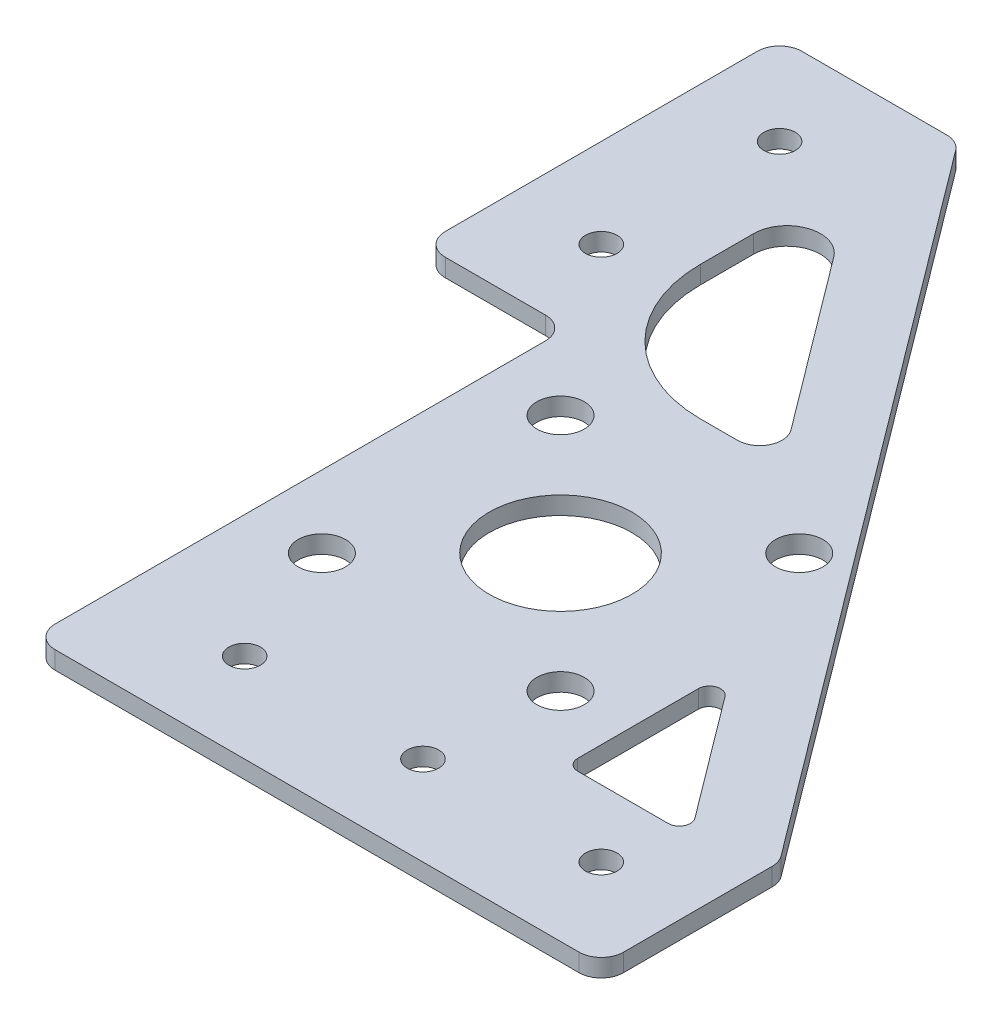
SolidWorks part; units mm, degrees
material "6061-O (SS)"
ref_plane "Front Plane" through (0, 0, 0) normal (0, 0, 1) x (1, 0, 0)
ref_plane "Top Plane" through (0, 0, 0) normal (0, 1, 0) x (1, 0, 0)
ref_plane "Right Plane" through (0, 0, 0) normal (1, 0, 0) x (0, 0, -1)
sketch "Sketch1" plane through (0, 0, 0) normal (0, 1, 0) x (1, 0, 0)
  line L6 (26.3525, 125.73) -> (100.965, 26.2467)
  line L19 (254, 25.4) -> (-431.8, 25.4) construction
  line L22 (254, 0) -> (-431.8, 0) construction
  line L23 (98.425, 0) -> (23.8125, 0)
  line L26 (0, 79.375) -> (0, 123.825)
  line L28 (0, 25.4) -> (0, 787.4) construction
  line L31 (3.175, 127) -> (23.8125, 127)
  line L33 (25.4, 25.4) -> (25.4, 787.4) construction
  line L35 (101.6, 3.175) -> (101.6, 24.3417)
  line L37 (17.4625, 76.2) -> (3.175, 76.2)
  line L38 (20.6375, 73.025) -> (20.6375, 3.175)
  arc A0 (12.7762, 112.2313) -> (12.7762, 116.3687) centre (12.7, 114.3) ccw construction
  arc A1 (12.6238, 90.9687) -> (12.6238, 86.8313) centre (12.7, 88.9) ccw construction
  arc A4 (90.9687, 12.7762) -> (86.8313, 12.7762) centre (88.9, 12.7) ccw construction
  arc A5 (17.4625, 76.2) -> (20.6375, 73.025) centre (17.4625, 73.025) cw
  arc A6 (3.175, 76.2) -> (0, 79.375) centre (3.175, 79.375) cw
  circle A13 centre (47.9, 47.9) radius 29.46 construction
  arc A14 (98.425, 0) -> (101.6, 3.175) centre (98.425, 3.175) ccw
  arc A15 (100.965, 26.2467) -> (101.6, 24.3417) centre (98.425, 24.3417) cw
  arc A16 (20.6375, 3.175) -> (23.8125, 0) centre (23.8125, 3.175) ccw
  arc A17 (0, 123.825) -> (3.175, 127) centre (3.175, 123.825) cw
  arc A18 (26.3525, 125.73) -> (23.8125, 127) centre (23.8125, 123.825) ccw
  point P7 (101.6, 25.4)
  point P14 (101.6, 25.4)
  point P38 (0, 127)
  point P42 (25.4, 127)
  point P43 (0, 0)
  dimension "D2" = 12.7
  dimension "D5" = 3.175
  dimension "D6" = 58.92
  dimension "D7" = 3.175
  dimension "D1" = 4.7625
  dimension "D3" = 12.7
  dimension "D4" = 12.7
extrude "Boss-Extrude1" add sketch "Sketch1" along normal blind 2.54
hole_wizard "#8 Clearance Hole1" positions "Sketch2" profile "Sketch3" hole size "#8" standard "ANSI Inch" end condition through all
sketch "Sketch2" plane through (0, 0, 0) normal (0, 1, 0) x (1, 0, 0)
  arc A0 (36.0313, 12.6238) -> (40.1687, 12.6238) centre (38.1, 12.7) ccw construction
  arc A1 (61.4313, 12.6238) -> (65.5687, 12.6238) centre (63.5, 12.7) ccw construction
  arc A3 (86.8313, 12.6238) -> (90.9687, 12.6238) centre (88.9, 12.7) ccw construction
  arc A4 (12.7762, 86.8313) -> (12.7762, 90.9687) centre (12.7, 88.9) ccw construction
  arc A5 (12.7762, 112.2313) -> (12.7762, 116.3687) centre (12.7, 114.3) ccw construction
  point P0 (38.1, 12.7)
  point P2 (63.5, 12.7)
  point P21 (88.9, 12.7)
  point P32 (12.7, 88.9)
  point P35 (12.7, 114.3)
sketch "Sketch3" plane through (38.1, 0, -12.7) normal (1, 0, 0) x (0, 0, -1)
  line L0 (0, 0) -> (0, 2.54)
  line L1 (0, 2.54) -> (2.2479, 2.54)
  line L2 (2.2479, 2.54) -> (2.2479, 0)
  line L5 (2.2479, 0) -> (0, 0)
  line L11 (0, -6.35) -> (0, 107.95) construction
  dimension "Thru Hole Dia." = 4.4958
  dimension "Thru Hole Depth" = 2.54
hole_wizard "1/4 Clearance Hole1" positions "Sketch4" profile "Sketch5" hole size "1/4" standard "ANSI Inch" end condition through all
sketch "Sketch4" plane through (0, 0, 0) normal (0, 1, 0) x (1, 0, 0)
  arc A2 (30.9, 34.075) -> (33.1451, 33.1451) centre (30.9, 30.9) ccw construction
  arc A5 (30.9, 68.075) -> (33.1451, 67.1451) centre (30.9, 64.9) ccw construction
  arc A6 (64.9, 68.075) -> (67.1451, 67.1451) centre (64.9, 64.9) ccw construction
  arc A7 (64.9, 34.075) -> (67.1451, 33.1451) centre (64.9, 30.9) ccw construction
  point P0 (30.9, 64.9)
  point P2 (30.9, 30.9)
  point P4 (64.9, 30.9)
  point P6 (64.9, 64.9)
sketch "Sketch5" plane through (30.9, 0, -64.9) normal (1, 0, 0) x (0, 0, -1)
  line L0 (0, 0) -> (0, 2.54)
  line L1 (0, 2.54) -> (3.3782, 2.54)
  line L2 (3.3782, 2.54) -> (3.3782, 0)
  line L5 (3.3782, 0) -> (0, 0)
  line L11 (0, -6.35) -> (0, 107.95) construction
  dimension "Thru Hole Dia." = 6.7564
  dimension "Thru Hole Depth" = 2.54
sketch "Sketch6" plane through (0, 0, 0) normal (0, -1, 0) x (1, 0, 0)
  line L0 (76.0125, -22.225) -> (88.9, -22.225)
  line L1 (74.425, -23.8125) -> (74.425, -40.9958)
  line L5 (90.17, -24.765) -> (77.2825, -41.9483)
  line L8 (30.7975, -103.9283) -> (49.115, -79.505)
  line L11 (46.575, -74.425) -> (41.275, -74.425)
  line L14 (22.225, -93.475) -> (22.225, -101.0708)
  line L15 (26.3525, -125.73) -> (100.965, -26.2467) construction
  circle A0 centre (47.9, -47.9) radius 10.16
  circle A1 centre (64.9, -30.9) radius 3.3782 construction
  circle A2 centre (88.9, -12.7) radius 2.2479 construction
  arc A3 (74.425, -40.9958) -> (77.2825, -41.9483) centre (76.0125, -40.9958) ccw
  arc A4 (74.425, -23.8125) -> (76.0125, -22.225) centre (76.0125, -23.8125) cw
  arc A5 (88.9, -22.225) -> (90.17, -24.765) centre (88.9, -23.8125) cw
  circle A6 centre (30.9, -64.9) radius 3.3782 construction
  circle A7 centre (12.7, -88.9) radius 2.2479 construction
  arc A8 (30.7975, -103.9283) -> (22.225, -101.0708) centre (26.9875, -101.0708) cw
  arc A9 (41.275, -74.425) -> (22.225, -93.475) centre (41.275, -93.475) ccw
  arc A10 (49.115, -79.505) -> (46.575, -74.425) centre (46.575, -77.6) ccw
  dimension "D1" = 20.32
  dimension "D4" = 9.525
  dimension "D5" = 1.5875
  dimension "D8" = 4.7625
  dimension "D9" = 19.05
  dimension "D10" = 3.175
  dimension "D2" = 9.525
  dimension "D3" = 9.525
  dimension "D6" = 9.525
  dimension "D7" = 9.525
extrude "Cut-Extrude1" cut sketch "Sketch6" against normal through all
